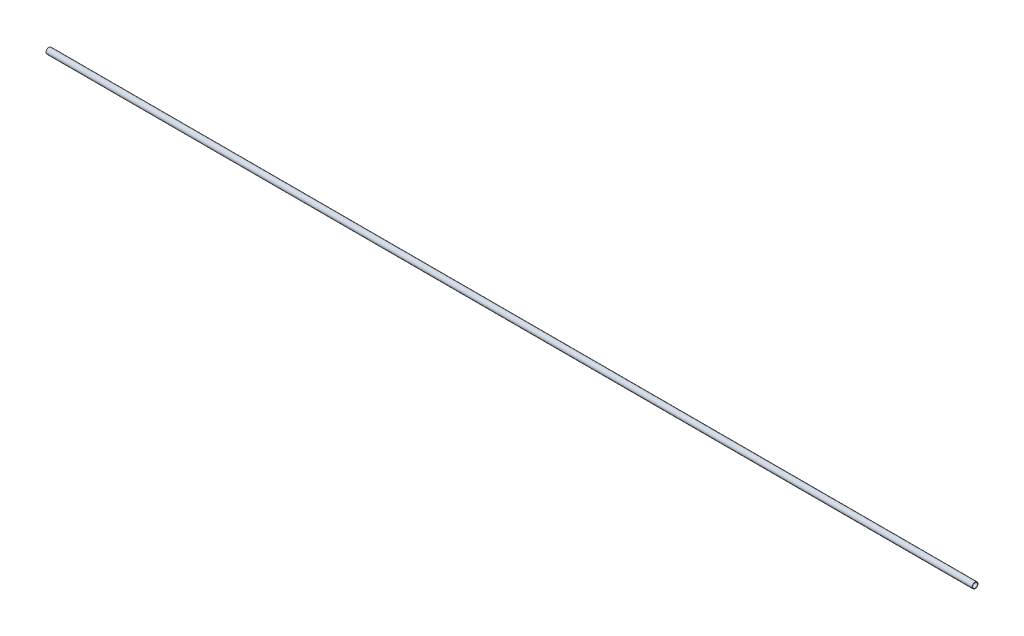
SolidWorks part; units mm, degrees
material "PF"
ref_plane "Front Plane" through (0, 0, 0) normal (0, 0, 1) x (1, 0, 0)
ref_plane "Top Plane" through (0, 0, 0) normal (0, 1, 0) x (1, 0, 0)
ref_plane "Right Plane" through (0, 0, 0) normal (1, 0, 0) x (0, 0, -1)
sketch "Sketch1" plane through (0, 0, 0) normal (1, 0, 0) x (0, 0, -1)
  circle A0 centre (0, 0) radius 3.81
  dimension "D1" = 7.62
extrude "Boss-Extrude1" add sketch "Sketch1" along normal blind 1219.2
sketch "Sketch2" plane through (0, 0, 0) normal (-1, 0, 0) x (0, 0, 1)
  circle A0 centre (0, 0) radius 3.175
  dimension "D1" = 6.35
extrude "Cut-Extrude1" cut sketch "Sketch2" against normal through all
